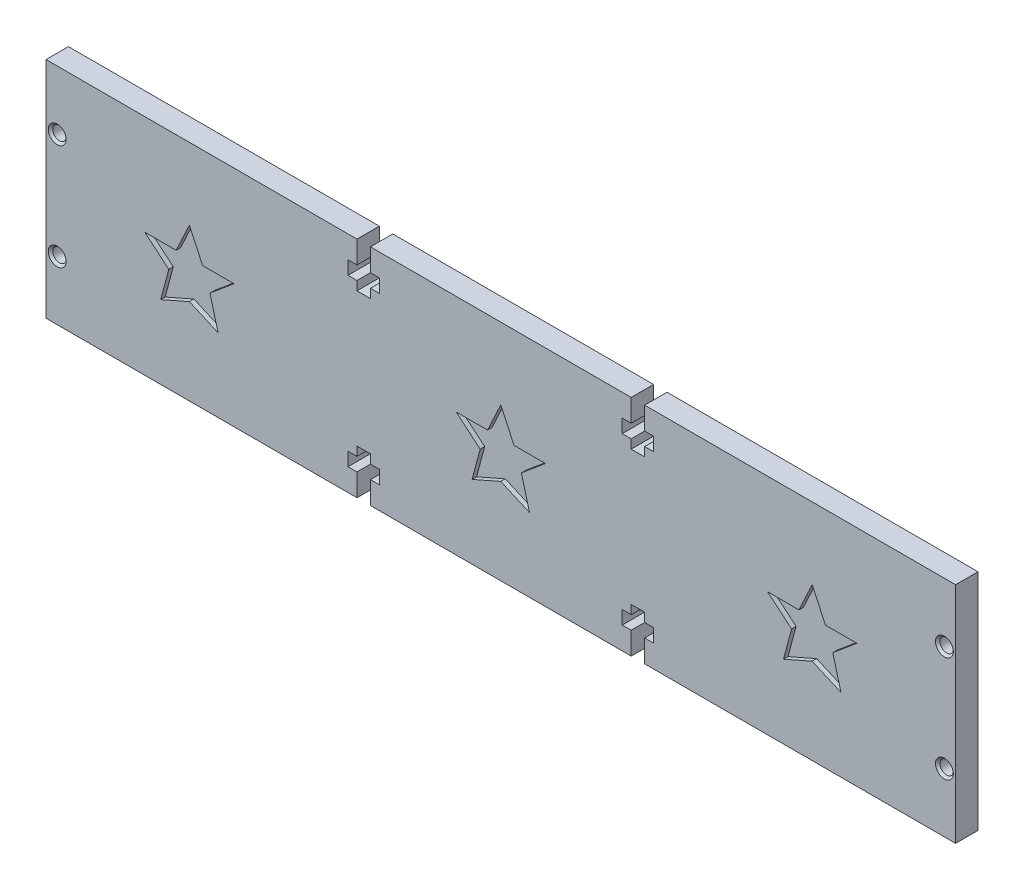
SolidWorks part; units mm, degrees
ref_plane "Front Plane" through (0, 0, 0) normal (0, 0, 1) x (1, 0, 0)
ref_plane "Top Plane" through (0, 0, 0) normal (0, 1, 0) x (1, 0, 0)
ref_plane "Right Plane" through (0, 0, 0) normal (1, 0, 0) x (0, 0, -1)
sketch "Sketch1" plane through (0, 0, 0) normal (0, 0, 1) x (1, 0, 0)
  line L1 (0, 0) -> (257.81, 0)
  line L2 (0, 0) -> (0, -63.5)
  line L3 (0, -63.5) -> (257.81, -63.5)
  line L4 (257.81, 0) -> (257.81, -63.5)
  dimension "D1" = 63.5
  dimension "D2" = 257.81
extrude "Boss-Extrude1" add sketch "Sketch1" along normal blind 6.35
sketch "Sketch4" plane through (0, 0, 6.35) normal (0, 0, 1) x (1, 0, 0)
  line L0 (128.905, 0) -> (128.905, -63.5) construction
  line L1 (257.81, 0) -> (0, 0) construction
  line L2 (0, -63.5) -> (257.81, -63.5) construction
  line L3 (128.905, -20.32) -> (125.1479, -28.3771)
  line L4 (125.1479, -28.3771) -> (116.2579, -28.3771)
  line L5 (116.2579, -28.3771) -> (123.0681, -34.0915)
  line L6 (123.0681, -34.0915) -> (120.7672, -42.6785)
  line L7 (120.7672, -42.6785) -> (128.905, -39.0998)
  line L8 (128.905, -39.0998) -> (137.0428, -42.6785)
  line L9 (137.0428, -42.6785) -> (134.7419, -34.0915)
  line L10 (134.7419, -34.0915) -> (141.5521, -28.3771)
  line L11 (141.5521, -28.3771) -> (132.6621, -28.3771)
  line L12 (132.6621, -28.3771) -> (128.905, -20.32)
  line L13 (60.96, 0) -> (60.96, -63.5) construction
  line L14 (257.81, 0) -> (0, 0) construction
  line L15 (0, -63.5) -> (257.81, -63.5) construction
  line L16 (20.32, 0) -> (20.32, -63.5) construction
  line L17 (40.64, 0) -> (40.64, -63.5) construction
  line L18 (196.85, 0) -> (196.85, -63.5) construction
  line L19 (257.81, 0) -> (0, 0) construction
  line L20 (0, -63.5) -> (257.81, -63.5) construction
  line L21 (217.17, 0) -> (217.17, -63.5) construction
  line L22 (237.49, 0) -> (237.49, -63.5) construction
  line L23 (0, 0) -> (0, -63.5) construction
  line L24 (257.81, -63.5) -> (257.81, 0) construction
  line L25 (217.17, -20.32) -> (213.4129, -28.3771)
  line L26 (213.4129, -28.3771) -> (204.5229, -28.3771)
  line L27 (204.5229, -28.3771) -> (211.3331, -34.0915)
  line L28 (211.3331, -34.0915) -> (209.0322, -42.6785)
  line L29 (209.0322, -42.6785) -> (217.17, -39.0998)
  line L30 (217.17, -39.0998) -> (225.3078, -42.6785)
  line L31 (225.3078, -42.6785) -> (223.0069, -34.0915)
  line L32 (223.0069, -34.0915) -> (229.8171, -28.3771)
  line L33 (229.8171, -28.3771) -> (220.9271, -28.3771)
  line L34 (220.9271, -28.3771) -> (217.17, -20.32)
  line L45 (40.64, -20.32) -> (36.8829, -28.3771)
  line L46 (36.8829, -28.3771) -> (27.9929, -28.3771)
  line L47 (27.9929, -28.3771) -> (34.8031, -34.0915)
  line L48 (34.8031, -34.0915) -> (32.5022, -42.6785)
  line L49 (32.5022, -42.6785) -> (40.64, -39.0998)
  line L50 (40.64, -39.0998) -> (48.7778, -42.6785)
  line L51 (48.7778, -42.6785) -> (46.4769, -34.0915)
  line L52 (46.4769, -34.0915) -> (53.2871, -28.3771)
  line L53 (53.2871, -28.3771) -> (44.3971, -28.3771)
  line L54 (44.3971, -28.3771) -> (40.64, -20.32)
  dimension "D1" = 8.89
  dimension "D2" = 8.89
  dimension "D3" = 25
  dimension "D4" = 25
  dimension "D5" = 20.32
  dimension "D6" = 8.89
  dimension "D7" = 8.89
  dimension "D8" = 8.89
  dimension "D9" = 8.89
  dimension "D10" = 8.89
  dimension "D11" = 8.89
  dimension "D12" = 8.89
  dimension "D13" = 40
  dimension "D14" = 40
  dimension "D15" = 8.89
  dimension "D16" = 115
  dimension "D17" = 20.32
  dimension "D18" = 20.32
  dimension "D19" = 20.32
  dimension "D20" = 20.32
  dimension "D21" = 20.32
  dimension "D22" = 20.32
  dimension "D23" = 8.89
  dimension "D24" = 8.89
  dimension "D25" = 8.89
  dimension "D26" = 8.89
  dimension "D27" = 8.89
  dimension "D28" = 8.89
  dimension "D29" = 8.89
  dimension "D30" = 8.89
  dimension "D31" = 40
  dimension "D32" = 115
  dimension "D33" = 40
  dimension "D34" = 20.32
  dimension "D35" = 8.89
  dimension "D36" = 25
  dimension "D37" = 25
  dimension "D38" = 66.262
  dimension "D39" = 25
  dimension "D40" = 25
  dimension "D41" = 20.32
  dimension "D42" = 66.262
  dimension "D43" = 8.89
  dimension "D44" = 8.89
  dimension "D45" = 8.89
  dimension "D46" = 8.89
  dimension "D47" = 8.89
  dimension "D48" = 8.89
  dimension "D49" = 8.89
  dimension "D50" = 8.89
  dimension "D51" = 8.89
  dimension "D52" = 8.89
  dimension "D53" = 40
  dimension "D54" = 115
  dimension "D55" = 40
extrude "Cut-Extrude2" cut sketch "Sketch4" against normal blind 1.27
sketch "Sketch6" plane through (0, 0, 6.35) normal (0, 0, 1) x (1, 0, 0)
  line L0 (88.138, -6.35) -> (91.948, -6.35) construction
  line L1 (88.138, 0) -> (91.948, 0)
  line L2 (88.138, 0) -> (88.138, -6.35)
  line L3 (88.138, -12.7) -> (91.948, -12.7)
  line L4 (91.948, 0) -> (91.948, -6.35)
  line L5 (85.598, -6.35) -> (88.138, -6.35)
  line L6 (85.598, -6.35) -> (85.598, -10.16)
  line L7 (85.598, -10.16) -> (88.138, -10.16)
  line L8 (94.488, -6.35) -> (94.488, -10.16)
  line L9 (91.948, -6.35) -> (94.488, -6.35)
  line L10 (88.138, -10.16) -> (91.948, -10.16) construction
  line L11 (91.948, -10.16) -> (94.488, -10.16)
  line L12 (88.138, -6.35) -> (88.138, -10.16) construction
  line L13 (88.138, -10.16) -> (88.138, -12.7)
  line L14 (91.948, -6.35) -> (91.948, -10.16) construction
  line L15 (91.948, -10.16) -> (91.948, -12.7)
  line L16 (165.862, -6.35) -> (169.672, -6.35) construction
  line L17 (165.862, 0) -> (169.672, 0)
  line L18 (165.862, 0) -> (165.862, -6.35)
  line L19 (165.862, -12.7) -> (169.672, -12.7)
  line L20 (169.672, 0) -> (169.672, -6.35)
  line L21 (163.322, -6.35) -> (165.862, -6.35)
  line L22 (163.322, -6.35) -> (163.322, -10.16)
  line L23 (163.322, -10.16) -> (165.862, -10.16)
  line L24 (172.212, -6.35) -> (172.212, -10.16)
  line L25 (169.672, -6.35) -> (172.212, -6.35)
  line L26 (165.862, -10.16) -> (169.672, -10.16) construction
  line L27 (169.672, -10.16) -> (172.212, -10.16)
  line L28 (165.862, -6.35) -> (165.862, -10.16) construction
  line L29 (165.862, -10.16) -> (165.862, -12.7)
  line L30 (169.672, -6.35) -> (169.672, -10.16) construction
  line L31 (169.672, -10.16) -> (169.672, -12.7)
  line L32 (88.138, -57.15) -> (91.948, -57.15) construction
  line L33 (88.138, -63.5) -> (91.948, -63.5)
  line L34 (88.138, -63.5) -> (88.138, -57.15)
  line L35 (88.138, -50.8) -> (91.948, -50.8)
  line L36 (91.948, -63.5) -> (91.948, -57.15)
  line L37 (85.598, -53.34) -> (88.138, -53.34)
  line L38 (85.598, -53.34) -> (85.598, -57.15)
  line L39 (85.598, -57.15) -> (88.138, -57.15)
  line L40 (94.488, -53.34) -> (94.488, -57.15)
  line L41 (91.948, -57.15) -> (94.488, -57.15)
  line L42 (88.138, -53.34) -> (91.948, -53.34) construction
  line L43 (91.948, -53.34) -> (94.488, -53.34)
  line L44 (88.138, -57.15) -> (88.138, -53.34) construction
  line L45 (88.138, -53.34) -> (88.138, -50.8)
  line L46 (91.948, -57.15) -> (91.948, -53.34) construction
  line L47 (91.948, -53.34) -> (91.948, -50.8)
  line L48 (165.862, -57.15) -> (169.672, -57.15) construction
  line L49 (165.862, -63.5) -> (169.672, -63.5)
  line L50 (165.862, -63.5) -> (165.862, -57.15)
  line L51 (165.862, -50.8) -> (169.672, -50.8)
  line L52 (169.672, -63.5) -> (169.672, -57.15)
  line L53 (163.322, -53.34) -> (165.862, -53.34)
  line L54 (163.322, -53.34) -> (163.322, -57.15)
  line L55 (163.322, -57.15) -> (165.862, -57.15)
  line L56 (172.212, -53.34) -> (172.212, -57.15)
  line L57 (169.672, -57.15) -> (172.212, -57.15)
  line L58 (165.862, -53.34) -> (169.672, -53.34) construction
  line L59 (169.672, -53.34) -> (172.212, -53.34)
  line L60 (165.862, -57.15) -> (165.862, -53.34) construction
  line L61 (165.862, -53.34) -> (165.862, -50.8)
  line L62 (169.672, -57.15) -> (169.672, -53.34) construction
  line L63 (169.672, -53.34) -> (169.672, -50.8)
  line L64 (128.905, 0) -> (128.905, -63.5) construction
  line L65 (0, -63.5) -> (257.81, -63.5) construction
  line L66 (257.81, 0) -> (0, 0) construction
  line L67 (0, 0) -> (0, -63.5) construction
  point P48 (90.043, -12.7)
  point P49 (167.767, -12.7)
  point P50 (90.043, -50.8)
  point P51 (167.767, -50.8)
  dimension "D1" = 12.7
  dimension "D2" = 3.81
  dimension "D3" = 3.81
  dimension "D4" = 8.89
  dimension "D5" = 2.54
  dimension "D6" = 12.7
  dimension "D7" = 3.81
  dimension "D8" = 3.81
  dimension "D9" = 2.54
  dimension "D10" = 8.89
  dimension "D11" = 12.7
  dimension "D12" = 3.81
  dimension "D13" = 2.54
  dimension "D14" = 3.81
  dimension "D15" = 8.89
  dimension "D16" = 3.81
  dimension "D17" = 12.7
  dimension "D18" = 3.81
  dimension "D19" = 8.89
  dimension "D20" = 2.54
  dimension "D21" = 77.724
  dimension "D22" = 77.724
  dimension "D23" = 6.35
  dimension "D24" = 38.862
  dimension "D25" = 6.35
  dimension "D26" = 6.35
  dimension "D27" = 6.35
  dimension "D28" = 38.862
  dimension "D29" = 90.043
extrude "Cut-Extrude3" cut sketch "Sketch6" against normal through all
sketch "Sketch7" plane through (0, 0, 6.35) normal (0, 0, 1) x (1, 0, 0)
  line L0 (0, -16.764) -> (257.81, -16.764) construction
  line L1 (0, 0) -> (0, -63.5) construction
  line L2 (257.81, -63.5) -> (257.81, 0) construction
  line L3 (0, -46.736) -> (257.81, -46.736) construction
  line L4 (3.175, 0) -> (3.175, -63.5) construction
  line L5 (88.138, 0) -> (0, 0) construction
  line L6 (0, -63.5) -> (88.138, -63.5) construction
  line L7 (254.635, 0) -> (254.635, -63.5) construction
  line L8 (257.81, 0) -> (169.672, 0) construction
  line L9 (169.672, -63.5) -> (257.81, -63.5) construction
  point P20 (3.175, -16.764)
  point P21 (3.175, -46.736)
  point P22 (254.635, -16.764)
  point P23 (254.635, -46.736)
  dimension "D1" = 16.764
  dimension "D2" = 16.764
  dimension "D3" = 3.175
  dimension "D4" = 3.175
hole_wizard "#6 Clearance Hole1" positions "Sketch8" profile "Sketch9" hole size "#6" standard "ANSI Inch" end condition through all
sketch "Sketch8" plane through (0, 0, 6.35) normal (0, 0, 1) x (1, 0, 0)
  point P0 (3.175, -16.764)
  point P3 (3.175, -46.736)
  point P6 (254.635, -46.736)
  point P9 (254.635, -16.764)
sketch "Sketch9" plane through (3.175, -16.764, 6.35) normal (1, 0, 0) x (0, -1, 0)
  line L0 (0, 0) -> (0, 6.35)
  line L1 (0, 6.35) -> (1.8986, 6.35)
  line L2 (1.8986, 6.35) -> (1.8986, 0.635)
  line L3 (1.8986, 0.635) -> (2.5337, 0)
  line L5 (2.5337, 0) -> (0, 0)
  line L6 (-1.8986, 0.635) -> (-2.5337, 0) construction
  line L11 (0, -6.35) -> (0, 107.95) construction
  dimension "Thru Hole Dia." = 3.7973
  dimension "Thru Hole Depth" = 6.35
  dimension "Near C'Sink Dia." = 5.0673
  dimension "Near C'Sink Angle" = 90
